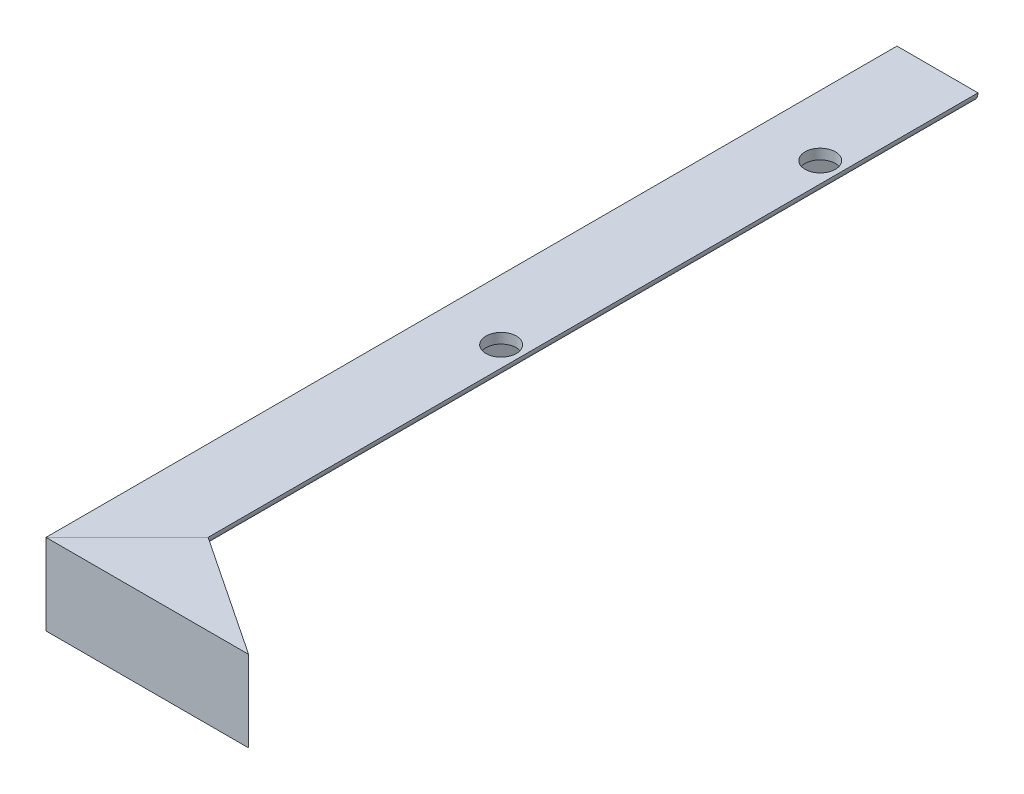
SolidWorks part; units mm, degrees
ref_plane "Alzado" through (0, 0, 0) normal (0, 0, 1) x (1, 0, 0)
ref_plane "Planta" through (0, 0, 0) normal (0, 1, 0) x (1, 0, 0)
ref_plane "Vista lateral" through (0, 0, 0) normal (1, 0, 0) x (0, 0, -1)
sketch3d "Croquis3D2"
  line L0 (0, 0, 0) -> (127, 0, 0)
  line L1 (0, 0, 0) -> (0, 0, -533.4)
  dimension "D1" = 533.4
  dimension "D2" = 127
other "Hierro angular 2 X 2 X 0.125(1)"
ref_plane "Plano1" through (0, 0, 0) normal (1, 0, 0) x (0, -1, 0)
sketch "Sketch1" plane through (0, 0, 0) normal (1, 0, 0) x (0, -1, 0)
  line L0 (0, 0) -> (0, 50.8)
  line L1 (0, 50.8) -> (0.0051, 50.8)
  line L2 (6.35, 44.4551) -> (6.35, 11.1125)
  line L3 (11.1125, 6.35) -> (44.4551, 6.35)
  line L4 (50.8, 0.0051) -> (50.8, 0)
  line L5 (50.8, 0) -> (0, 0)
  arc A0 (50.8, 0.0051) -> (44.4551, 6.35) centre (44.4551, 0.0051) ccw
  arc A1 (0.0051, 50.8) -> (6.35, 44.4551) centre (0.0051, 44.4551) cw
  arc A2 (11.1125, 6.35) -> (6.35, 11.1125) centre (11.1125, 11.1125) cw
  point P10 (25.4, 0)
  point P14 (0, 25.4)
  point P15 (6.35, 25.4)
  point P16 (25.4, 6.35)
  point P17 (6.35, 50.8)
  point P18 (50.8, 6.35)
  point P19 (0, 0)
  dimension "D2" = 0.0051
  dimension "Radius_1" = 4.7625
  dimension "D1" = 6.35
  dimension "H_leg" = 50.8
sketch "Croquis2" plane through (0, 0, 0) normal (0, 1, 0) x (1, 0, 0)
  line L0 (50.8, 533.4) -> (0, 533.4) construction
  line L1 (50.8, 50.8) -> (50.8, 533.4) construction
  circle A0 centre (38.1, 447.2) radius 9.525
  circle A1 centre (38.1, 247.2) radius 9.525
  dimension "D1" = 86.2
  dimension "D2" = 200
  dimension "D3" = 19.05
  dimension "D4" = 12.7
extrude "Cortar-Extruir1" cut sketch "Croquis2" against normal through all
sketch "Croquis3" plane through (0, 0, 0) normal (0, 1, 0) x (1, 0, 0)
  line L0 (127, 0) -> (50.8, 50.8)
  line L1 (50.8, 50.8) -> (127, 50.8)
  line L2 (127, 50.8) -> (127, 0)
extrude "Cortar-Extruir2" cut sketch "Croquis3" against normal blind 176.53
